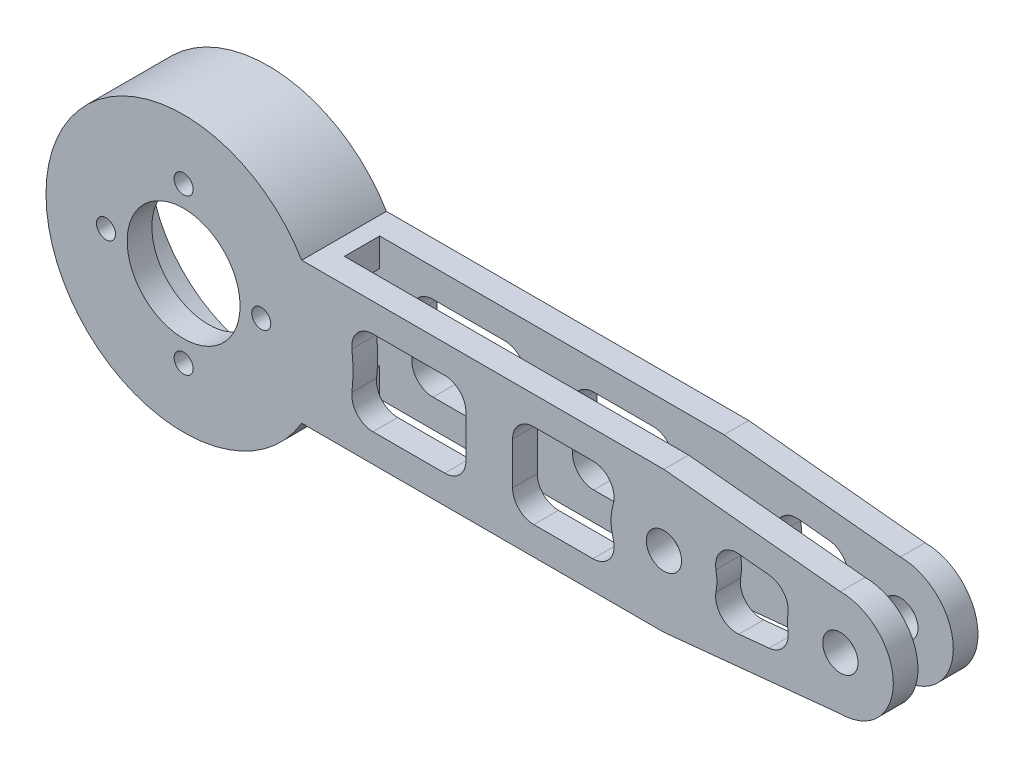
SolidWorks part; units mm, degrees
ref_plane "前视基准面" through (0, 0, 0) normal (0, 0, 1) x (1, 0, 0)
ref_plane "上视基准面" through (0, 0, 0) normal (0, 1, 0) x (1, 0, 0)
ref_plane "右视基准面" through (0, 0, 0) normal (1, 0, 0) x (0, 0, -1)
sketch "草图2" plane through (0, 0, 0) normal (0, 0, 1) x (1, 0, 0)
  line L5 (-28.2593, 10) -> (23.0621, 10)
  line L6 (23.0621, -10) -> (-28.2593, -10)
  line L9 (23.0621, 10) -> (48.0621, 7.5)
  line L10 (48.0621, -7.5) -> (23.0621, -10)
  circle A1 centre (-45, 0) radius 11 construction
  circle A2 centre (-34, 0) radius 1.35
  circle A3 centre (-45, 0) radius 11 construction
  circle A4 centre (-45, -11) radius 1.35
  circle A5 centre (-45, 0) radius 11 construction
  circle A6 centre (-56, 0) radius 1.35
  circle A7 centre (-45, 0) radius 11 construction
  circle A8 centre (-45, 11) radius 1.35
  circle A9 centre (48.0621, 0) radius 2.5
  circle A10 centre (23.0621, 0) radius 2.5
  arc A11 (48.0621, -7.5) -> (48.0621, 7.5) centre (48.0621, 0) ccw
  arc A12 (-28.2593, 10) -> (-28.2593, -10) centre (-45, 0) ccw
  point P0 (0, 0)
  point P24 (-45, 0)
  dimension "D5" = 22
  dimension "D6" = 2.7
  dimension "D8" = 5
  dimension "D9" = 5
  dimension "D11" = 15
  dimension "D2" = 39
  dimension "D1" = 20
  dimension "D4" = 45
  dimension "D10" = 25
  dimension "D7" = 4
extrude "凸台-拉伸1" add sketch "草图2" along normal blind 12
sketch "草图3" plane through (0, 10, 0) normal (0, 1, 0) x (1, 0, 0)
  line L0 (-64.5, -6) -> (70.3045, -6) construction
  line L1 (-64.5, 0) -> (-64.5, -12) construction
  line L2 (-25.7174, -3.5) -> (55.5621, -3.5)
  line L3 (55.5621, -12) -> (55.5621, 0) construction
  line L4 (55.5621, -3.5) -> (55.5621, -8.5)
  line L5 (55.5621, -8.5) -> (-25.7174, -8.5)
  line L6 (-25.7174, -8.5) -> (-25.7174, -3.5)
  dimension "D1" = 5
  dimension "D2" = 2.5
extrude "切除-拉伸1" cut sketch "草图3" against normal through all
sketch "草图4" plane through (0, 0, 12) normal (0, 0, 1) x (1, 0, 0)
  circle A0 centre (-45, 0) radius 16.9
  dimension "D1" = 33.8
extrude "切除-拉伸2" cut sketch "草图4" against normal blind 8.5
sketch "草图5" plane through (0, 0, 3.5) normal (0, 0, 1) x (1, 0, 0)
  circle A0 centre (-45, 0) radius 8
  dimension "D1" = 16
extrude "切除-拉伸3" cut sketch "草图5" against normal through all
sketch "草图7" plane through (-25.7174, 0, 0) normal (1, 0, 0) x (0, 0, -1)
  line L0 (-8.5, -6) -> (-3.5, -6)
  line L1 (-8.5, -10) -> (-8.5, 10) construction
  line L2 (-3.5, 7.5) -> (-3.5, -7.5) construction
  line L3 (-3.5, -6) -> (-3.5, 6)
  line L4 (-3.5, -10) -> (-3.5, 10) construction
  line L5 (-3.5, 6) -> (-8.5, 6)
  line L6 (-8.5, -7.5) -> (-8.5, 7.5) construction
  line L7 (-8.5, 6) -> (-8.5, -6)
  line L8 (0, 0) -> (-14.8358, 0) construction
  dimension "D1" = 12
  dimension "D2" = 6
extrude "切除-拉伸4" cut sketch "草图7" against normal up to next
sketch "草图8" plane through (0, 0, 12) normal (0, 0, 1) x (1, 0, 0)
  line L0 (-5, 3) -> (-5, -3)
  line L1 (-18.1672, 6) -> (-8, 6)
  line L2 (-18.1672, -6) -> (-8, -6)
  line L3 (23.0621, 10) -> (-28.2593, 10) construction
  line L4 (-28.2593, -10) -> (23.0621, -10) construction
  line L5 (1.6105, 3) -> (1.6105, -3)
  line L6 (4.6105, 6) -> (12.9998, 6)
  line L7 (4.6105, -6) -> (12.9998, -6)
  line L8 (33.6812, 4.9181) -> (37.969, 4.4894)
  line L9 (33.6812, -4.9181) -> (37.969, -4.4894)
  line L10 (48.0621, 7.5) -> (23.0621, 10) construction
  line L11 (23.0621, -10) -> (48.0621, -7.5) construction
  arc A0 (-21.1486, -2.6667) -> (-21.1486, 2.6667) centre (-45, 0) ccw
  arc A1 (-5, -3) -> (-8, -6) centre (-8, -3) cw
  arc A2 (-5, 3) -> (-8, 6) centre (-8, 3) ccw
  arc A3 (-18.1672, 6) -> (-21.1486, 2.6667) centre (-18.1672, 3) ccw
  arc A4 (-21.1486, -2.6667) -> (-18.1672, -6) centre (-18.1672, -3) ccw
  arc A5 (30.4339, -1.3807) -> (30.4339, 1.3807) centre (23.0621, 0) ccw
  arc A6 (40.6395, 1.0745) -> (40.6395, -1.0745) centre (48.0621, 0) ccw
  arc A7 (15.8748, 2.1429) -> (15.8748, -2.1429) centre (23.0621, 0) ccw
  arc A8 (40.6395, 1.0745) -> (37.969, 4.4894) centre (37.6704, 1.5043) ccw
  arc A9 (40.6395, -1.0745) -> (37.969, -4.4894) centre (37.6704, -1.5043) cw
  arc A10 (30.4339, -1.3807) -> (33.6812, -4.9181) centre (33.3827, -1.933) ccw
  arc A11 (30.4339, 1.3807) -> (33.6812, 4.9181) centre (33.3827, 1.933) cw
  arc A12 (15.8748, 2.1429) -> (12.9998, 6) centre (12.9998, 3) ccw
  arc A13 (12.9998, -6) -> (15.8748, -2.1429) centre (12.9998, -3) ccw
  arc A14 (4.6105, -6) -> (1.6105, -3) centre (4.6105, -3) cw
  arc A15 (4.6105, 6) -> (1.6105, 3) centre (4.6105, 3) ccw
  dimension "D1" = 48
  dimension "D5" = 3
  dimension "D6" = 15
  dimension "D9" = 3
  dimension "D2" = 4
  dimension "D3" = 4
  dimension "D4" = 40
  dimension "D7" = 4
  dimension "D8" = 4
extrude "切除-拉伸6" cut sketch "草图8" against normal through all
sketch "草图9" plane through (0, 0, 3.5) normal (0, 0, 1) x (1, 0, 0)
  circle A1 centre (-34, 0) radius 1.35 construction
  circle A2 centre (-45, -11) radius 1.35 construction
  circle A3 centre (-56, 0) radius 1.35 construction
  circle A4 centre (-45, 11) radius 1.35 construction
  circle A5 centre (-45, 0) radius 8 construction
  circle A6 centre (-45, 0) radius 16.9
  circle A7 centre (-34, 0) radius 1.35
  circle A8 centre (-45, -11) radius 1.35
  circle A9 centre (-56, 0) radius 1.35
  circle A10 centre (-45, 11) radius 1.35
  circle A11 centre (-45, 0) radius 8
extrude "凸台-拉伸3" add sketch "草图9" along normal blind 8.5
sketch "草图10" plane through (0, 0, 0) normal (0, 0, -1) x (-1, 0, 0)
  circle A0 centre (45, 0) radius 16.9
  dimension "D1" = 33.8
extrude "切除-拉伸7" cut sketch "草图10" against normal blind 8.5
